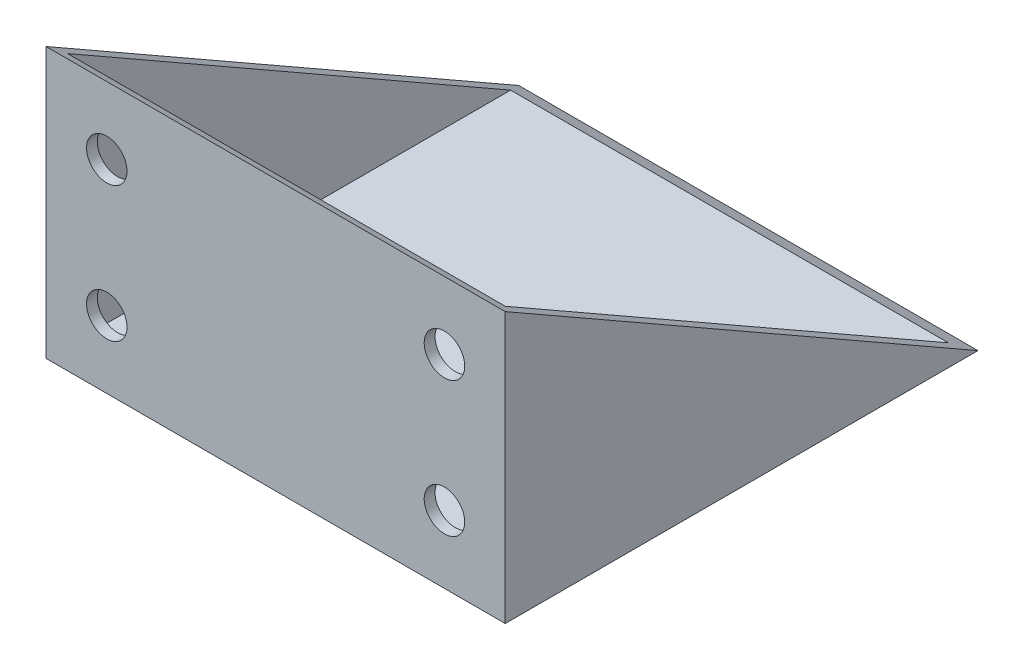
SolidWorks part; units mm, degrees
ref_plane "Alzado" through (0, 0, 0) normal (0, 0, 1) x (1, 0, 0)
ref_plane "Planta" through (0, 0, 0) normal (0, 1, 0) x (1, 0, 0)
ref_plane "Vista lateral" through (0, 0, 0) normal (1, 0, 0) x (0, 0, -1)
sketch "Croquis4" plane through (0, 0, 0) normal (1, 0, 0) x (0, 0, -1)
  line L0 (0, 0) -> (35, 0)
  line L1 (35, 0) -> (0, 20)
  line L2 (0, 20) -> (0, 0)
  dimension "D1" = 20
  dimension "D2" = 35
extrude "Saliente-Extruir3" add sketch "Croquis4" along normal blind 34
shell "Vaciado5" thickness 0.8
sketch "Croquis5" plane through (0, 0, 0) normal (0, 0, 1) x (1, 0, 0)
  line L0 (0, 0) -> (34, 20) construction
  line L2 (29.5, 5) -> (4.5, 5)
  line L3 (29.5, 5) -> (29.5, 15)
  line L4 (29.5, 15) -> (4.5, 15)
  line L5 (4.5, 5) -> (4.5, 15)
  line L6 (29.5, 5) -> (4.5, 15) construction
  line L7 (29.5, 15) -> (4.5, 5) construction
  circle A0 centre (4.5, 15) radius 1.5
  circle A1 centre (29.5, 15) radius 1.5
  circle A2 centre (29.5, 5) radius 1.5
  circle A3 centre (4.5, 5) radius 1.5
  point P4 (17, 10)
  dimension "D3" = 2
  dimension "D1" = 25
  dimension "D2" = 10
  dimension "D4" = 2
extrude "Cortar-Extruir1" cut sketch "Croquis5" against normal blind 3 contours A0 | A3 | A1 | A2
